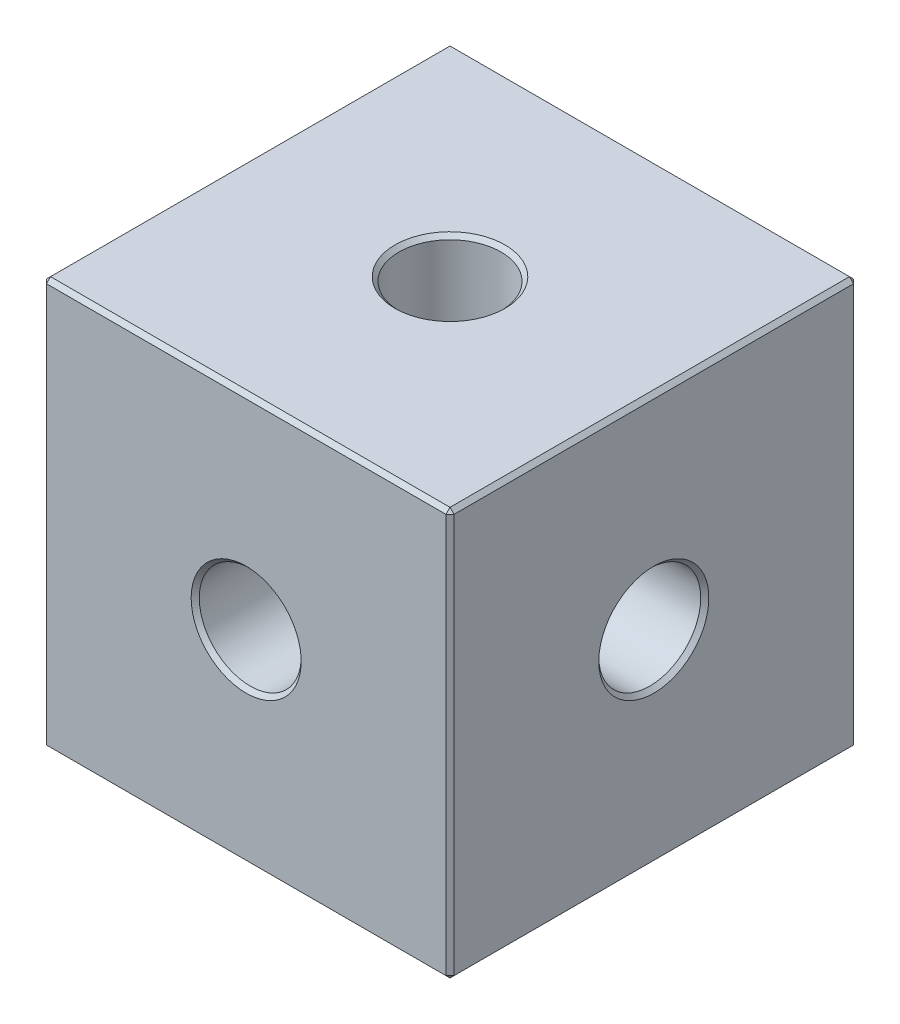
SolidWorks part; units mm, degrees
ref_plane "前视基准面" through (0, 0, 0) normal (0, 0, 1) x (1, 0, 0)
ref_plane "上视基准面" through (0, 0, 0) normal (0, 1, 0) x (1, 0, 0)
ref_plane "右视基准面" through (0, 0, 0) normal (1, 0, 0) x (0, 0, -1)
sketch "草图1" plane through (0, 0, 0) normal (0, 1, 0) x (1, 0, 0)
  line L1 (-10, 10) -> (10, 10)
  line L2 (-10, 10) -> (-10, -10)
  line L3 (-10, -10) -> (10, -10)
  line L4 (10, 10) -> (10, -10)
  line L5 (-10, 10) -> (10, -10) construction
  line L6 (-10, -10) -> (10, 10) construction
  point P0 (0, 0)
  dimension "D1" = 20
extrude "凸台-拉伸1" add sketch "草图1" along normal mid plane 20
hole_wizard "M6 螺纹孔1" positions "草图2" profile "草图3" tap size "M6" standard "GB" end condition through all
sketch "草图2" plane through (0, 0, 10) normal (0, 0, 1) x (1, 0, 0)
  point P0 (0, 0)
sketch "草图3" plane through (0, 0, 10) normal (1, 0, 0) x (0, -1, 0)
  line L0 (0, 0) -> (0, 20)
  line L1 (0, 20) -> (2.5, 20)
  line L2 (2.5, 20) -> (2.5, 0)
  line L5 (2.5, 0) -> (0, 0)
  line L11 (0, -6.35) -> (0, 107.95) construction
  dimension "通孔螺纹孔钻头直径" = 5
  dimension "通孔螺纹孔钻头深度" = 20
cosmetic thread "孔螺蚊线1" parameters "D2"=6
hole_wizard "M6 螺纹孔2" positions "草图4" profile "草图5" tap size "M6" standard "GB" end condition through all
sketch "草图4" plane through (0, 10, 0) normal (0, 1, 0) x (1, 0, 0)
  point P0 (0, 0)
sketch "草图5" plane through (0, 10, 0) normal (1, 0, 0) x (0, 0, 1)
  line L0 (0, 0) -> (0, 20)
  line L1 (0, 20) -> (2.5, 20)
  line L2 (2.5, 20) -> (2.5, 0)
  line L5 (2.5, 0) -> (0, 0)
  line L11 (0, -6.35) -> (0, 107.95) construction
  dimension "通孔螺纹孔钻头直径" = 5
  dimension "通孔螺纹孔钻头深度" = 20
cosmetic thread "孔螺蚊线2" parameters "D2"=6
hole_wizard "M6 螺纹孔3" positions "草图6" profile "草图7" tap size "M6" standard "GB" end condition through all
sketch "草图6" plane through (10, 0, 0) normal (1, 0, 0) x (0, 0, -1)
  point P0 (0, 0)
sketch "草图7" plane through (10, 0, 0) normal (0, 1, 0) x (0, 0, -1)
  line L0 (0, 0) -> (0, 20)
  line L1 (0, 20) -> (2.5, 20)
  line L2 (2.5, 20) -> (2.5, 0)
  line L5 (2.5, 0) -> (0, 0)
  line L11 (0, -6.35) -> (0, 107.95) construction
  dimension "通孔螺纹孔钻头直径" = 5
  dimension "通孔螺纹孔钻头深度" = 20
cosmetic thread "孔螺蚊线3" parameters "D2"=6
chamfer "倒角1" distance 0.2 angle 45 18 edges at (0, -10, 2.5) (-10, 0, -2.5) (2.5, 0, -10) (10, 0, -2.5) (2.5, 0, 10) (-10, -10, 0) (-10, 0, -10) (0, -10, -10) (10, 0, -10) (10, -10, 0) (-10, 0, 10) (0, -10, 10) (10, 0, 10) (0, 10, 10) (-10, 10, 0) (0, 10, -10) (10, 10, 0) (0, 10, 2.5)
